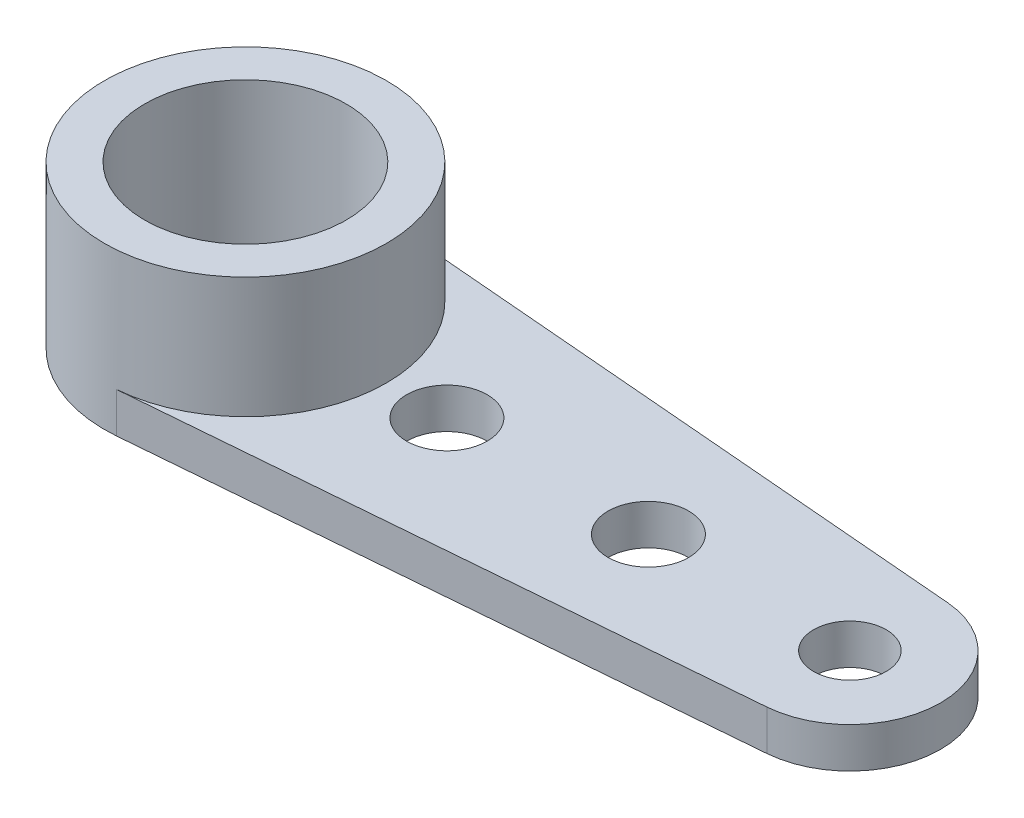
SolidWorks part; units mm, degrees
ref_plane "Front Plane" through (0, 0, 0) normal (0, 0, 1) x (1, 0, 0)
ref_plane "Top Plane" through (0, 0, 0) normal (0, 1, 0) x (1, 0, 0)
ref_plane "Right Plane" through (0, 0, 0) normal (1, 0, 0) x (0, 0, -1)
sketch "Sketch1" plane through (0, 0, 0) normal (0, 1, 0) x (1, 0, 0)
  line L0 (0.2917, 3.4878) -> (15.1875, 2.2422)
  line L1 (0.2917, -3.4878) -> (15.1875, -2.2422)
  circle A0 centre (0, 0) radius 3.5
  circle A1 centre (15, 0) radius 2.25
  dimension "D2" = 7
  dimension "D3" = 4.5
  dimension "D1" = 15
extrude "Boss-Extrude1" add sketch "Sketch1" along normal blind 1 contours A1 L0 A0 L1 | A0 | A1 L0
sketch "Sketch2" plane through (0, 1, 0) normal (0, 1, 0) x (1, 0, 0)
  circle A0 centre (0, 0) radius 3.5
extrude "Boss-Extrude2" add sketch "Sketch2" along normal blind 3
sketch "Sketch3" plane through (0, 4, 0) normal (0, 1, 0) x (1, 0, 0)
  circle A0 centre (0, 0) radius 2.5
  dimension "D1" = 5
extrude "Cut-Extrude1" cut sketch "Sketch3" against normal through all
sketch "Sketch4" plane through (0, 0, 0) normal (0, -1, 0) x (1, 0, 0)
  circle A0 centre (15, 0) radius 0.9
  dimension "D1" = 1.8
extrude "Cut-Extrude2" cut sketch "Sketch4" against normal through all
sketch "Sketch5" plane through (0, 0, 0) normal (0, -1, 0) x (1, 0, 0)
  line L0 (0, 0) -> (15, 0)
  circle A0 centre (5, 0) radius 1
  circle A1 centre (10, 0) radius 1
  dimension "D3" = 2
  dimension "D4" = 2
  dimension "D1" = 5
  dimension "D2" = 5
extrude "Cut-Extrude3" cut sketch "Sketch5" against normal through all contours L0 A0 | L0 A0 | L0 A1 | L0 A1
sketch "Sketch6" plane through (0, 4, 0) normal (0, 1, 0) x (1, 0, 0)
sketch "Sketch8" plane through (0.2917, 0, 3.4878) normal (0.0833, 0, 0.9965) x (0.9965, 0, -0.0833)
  line L0 (3.5, 4) -> (-3.5, 4) construction
  line L1 (-3.5, 0) -> (0.5813, 0) construction
